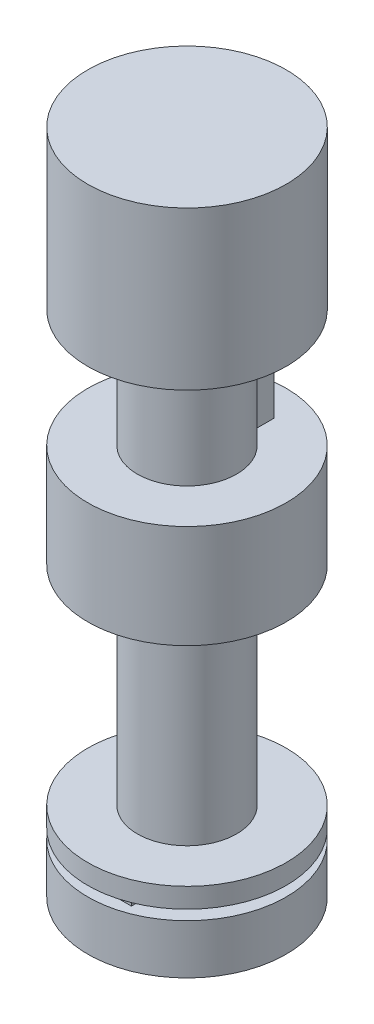
SolidWorks part; units mm, degrees
ref_plane "Front Plane" through (0, 0, 0) normal (0, 0, 1) x (1, 0, 0)
ref_plane "Top Plane" through (0, 0, 0) normal (0, 1, 0) x (1, 0, 0)
ref_plane "Right Plane" through (0, 0, 0) normal (1, 0, 0) x (0, 0, -1)
sketch "Sketch1" plane through (0, 0, 0) normal (0, 1, 0) x (1, 0, 0)
  line L0 (-2, 4.5826) -> (-2, 6.7826)
  line L1 (-2, 6.7826) -> (2, 6.7826)
  line L2 (2, 6.7826) -> (2, 4.5826)
  circle A0 centre (0, 0) radius 5
  arc A1 (-2, 4.5826) -> (2, 4.5826) centre (0, 0) cw
  dimension "D1" = 10
  dimension "D2" = 4
  dimension "D3" = 2.2
  dimension "D4" = 2.2
extrude "Boss-Extrude2" add sketch "Sketch1" along normal blind 11.9 contours A0 | A0 L2 L1 L0
sketch "Sketch3" plane through (0, 11.9, 0) normal (0, 1, 0) x (1, 0, 0)
  circle A0 centre (0, 0) radius 10
  dimension "D1" = 20
extrude "Boss-Extrude3" add sketch "Sketch3" along normal blind 15.9
sketch "Sketch5" plane through (0, 0, 0) normal (0, -1, 0) x (1, 0, 0)
  circle A0 centre (0, 0) radius 10
extrude "Boss-Extrude4" add sketch "Sketch5" along normal blind 10.4
sketch "Sketch6" plane through (0, -10.4, 0) normal (0, -1, 0) x (1, 0, 0)
  circle A0 centre (0, 0) radius 5
  dimension "D1" = 10
extrude "Boss-Extrude5" add sketch "Sketch6" along normal blind 23
sketch "Sketch7" plane through (0, -33.4, 0) normal (0, -1, 0) x (1, 0, 0)
  line L0 (-3, -9.5394) -> (-3, -14.3394)
  line L1 (-3, 14.3394) -> (3, 14.3394)
  line L2 (-3, 14.3394) -> (-3, 9.5394)
  line L3 (-3, -14.3394) -> (3, -14.3394)
  line L4 (3, 14.3394) -> (3, 9.5394)
  line L5 (3, -9.5394) -> (3, -14.3394)
  circle A0 centre (0, 0) radius 10
  circle M7 centre (0, 0) radius 5
  dimension "D7" = 20
  dimension "D1" = 6
  dimension "D2" = 4.8
  dimension "D3" = 4.8
  dimension "D4" = 6
  dimension "D5" = 4.8
  dimension "D6" = 4.8
extrude "Boss-Extrude6" add sketch "Sketch7" against normal blind 2 contours A0 M7
sketch "Sketch8" plane through (0, -33.4, 0) normal (0, -1, 0) x (1, 0, 0)
  line L0 (-3, -4) -> (-3, -8.6)
  line L1 (-3, 8.6) -> (3, 8.6)
  line L2 (-3, 8.6) -> (-3, 4)
  line L3 (-3, -8.6) -> (3, -8.6)
  line L4 (3, 8.6) -> (3, 4)
  line L5 (3, -4) -> (3, -8.6)
  circle A0 centre (0, 0) radius 5
  dimension "D1" = 10
  dimension "D2" = 6
  dimension "D3" = 4.6
  dimension "D4" = 4.6
  dimension "D5" = 6
  dimension "D6" = 4.6
  dimension "D7" = 4.6
extrude "Boss-Extrude7" add sketch "Sketch8" along normal blind 1 contours A0 | A0 L4 L1 L2 | A0 L0 L3 L5
sketch "Sketch9" plane through (0, -34.4, 0) normal (0, -1, 0) x (-1, 0, 0)
  circle A0 centre (0, 0) radius 10
  dimension "D1" = 20
extrude "Boss-Extrude8" add sketch "Sketch9" along normal blind 5
